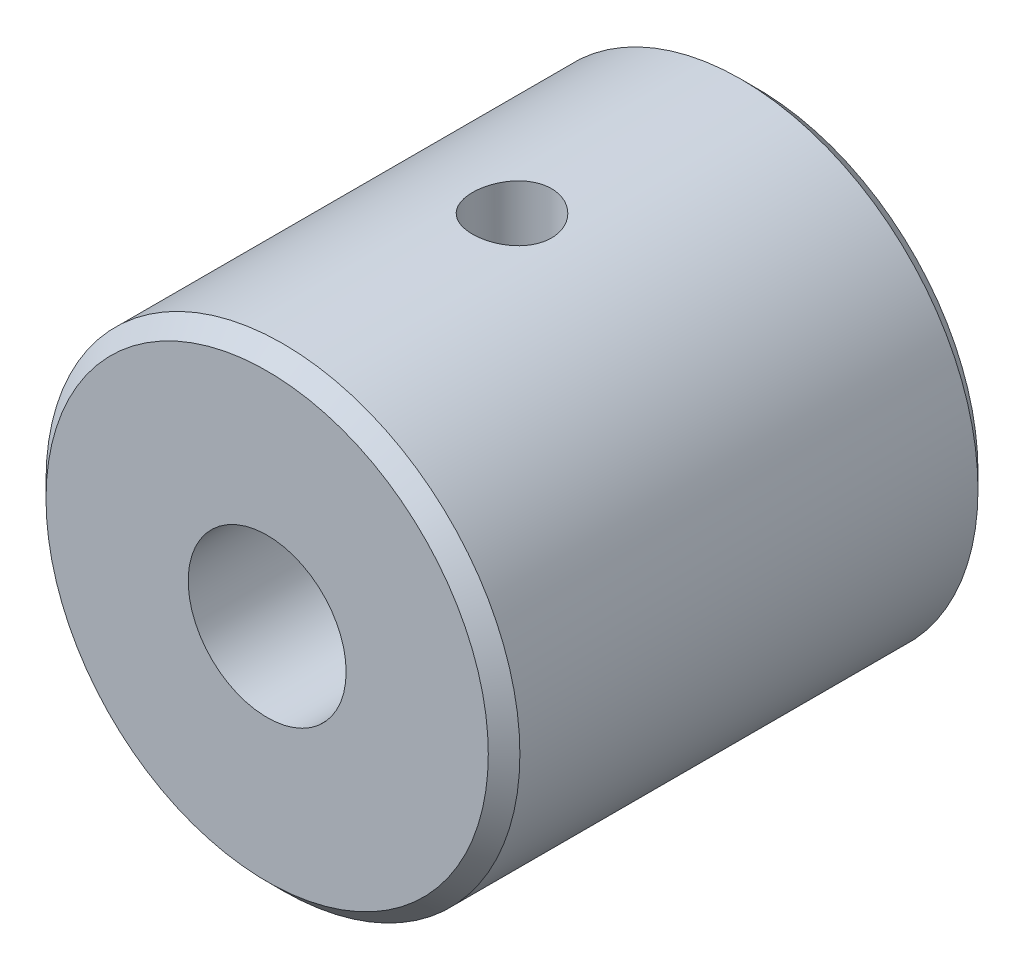
SolidWorks part; units mm, degrees
ref_plane "Front Plane" through (0, 0, 0) normal (0, 0, 1) x (1, 0, 0)
ref_plane "Top Plane" through (0, 0, 0) normal (0, 1, 0) x (1, 0, 0)
ref_plane "Right Plane" through (0, 0, 0) normal (1, 0, 0) x (0, 0, -1)
sketch "Sketch1" plane through (0, 0, 0) normal (0, 0, 1) x (1, 0, 0)
  circle A0 centre (0, 0) radius 3.81
  dimension "D1" = 7.62
extrude "Extrude1" add sketch "Sketch1" along normal mid plane 7.874
chamfer "Chamfer1" distance 0.254 angle 45 2 edges at (3.81, 0, -3.937) (3.81, 0, 3.937)
sketch "Sketch2" plane through (0, 0, 0) normal (0, 0, 1) x (1, 0, 0)
  circle A0 centre (0, 0) radius 1.27
  dimension "D1" = 2.54
extrude "Cut-Extrude1" cut sketch "Sketch2" against normal through all and the other way through all
sketch "Sketch3" plane through (0, 0, 0) normal (0, 1, 0) x (1, 0, 0)
  circle A0 centre (0, 0) radius 0.635
  dimension "D1" = 1.27
extrude "Cut-Extrude2" cut sketch "Sketch3" against normal through all and the other way through all
